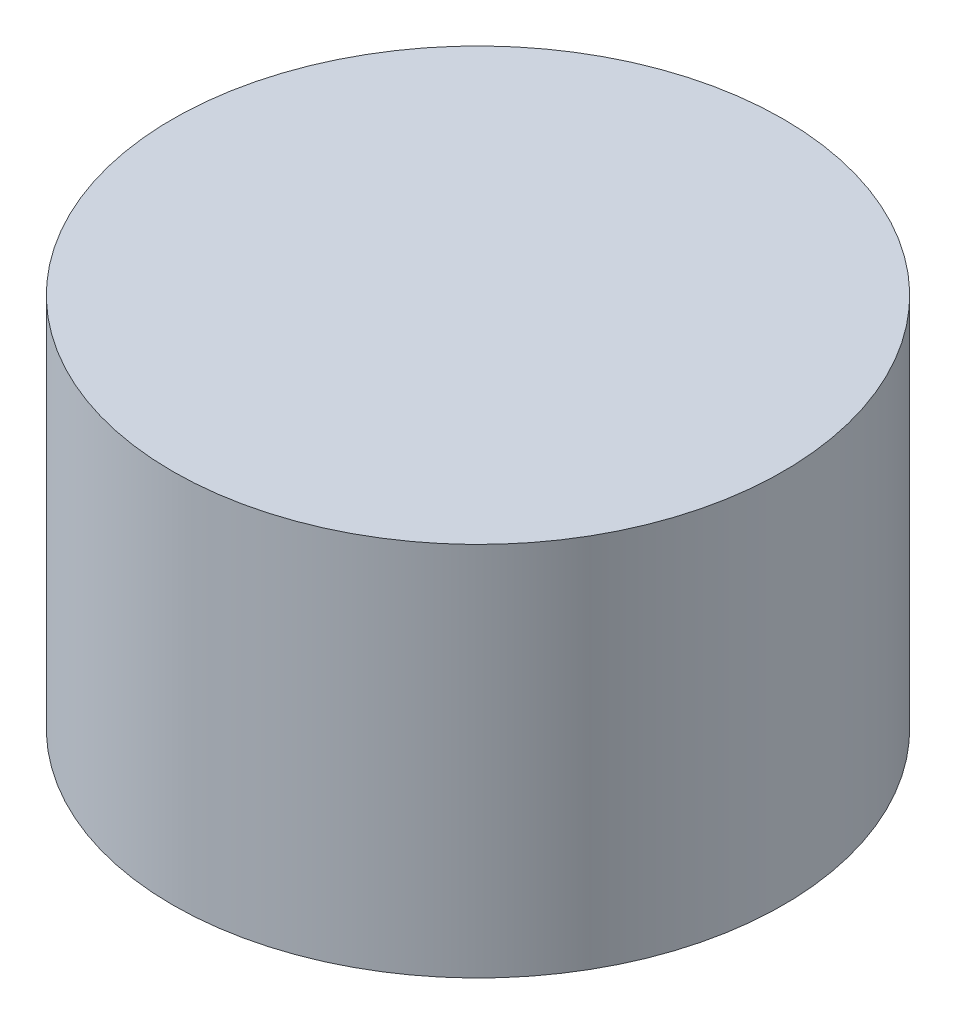
SolidWorks part; units mm, degrees
ref_plane "Спереди" through (0, 0, 0) normal (0, 0, 1) x (1, 0, 0)
ref_plane "Сверху" through (0, 0, 0) normal (0, 1, 0) x (1, 0, 0)
ref_plane "Справа" through (0, 0, 0) normal (1, 0, 0) x (0, 0, -1)
sketch "Эскиз1" plane through (0, 0, 0) normal (0, 1, 0) x (1, 0, 0)
  circle A0 centre (0, 0) radius 16.2592
extrude "Вытянуть1" add sketch "Эскиз1" along normal blind 20
